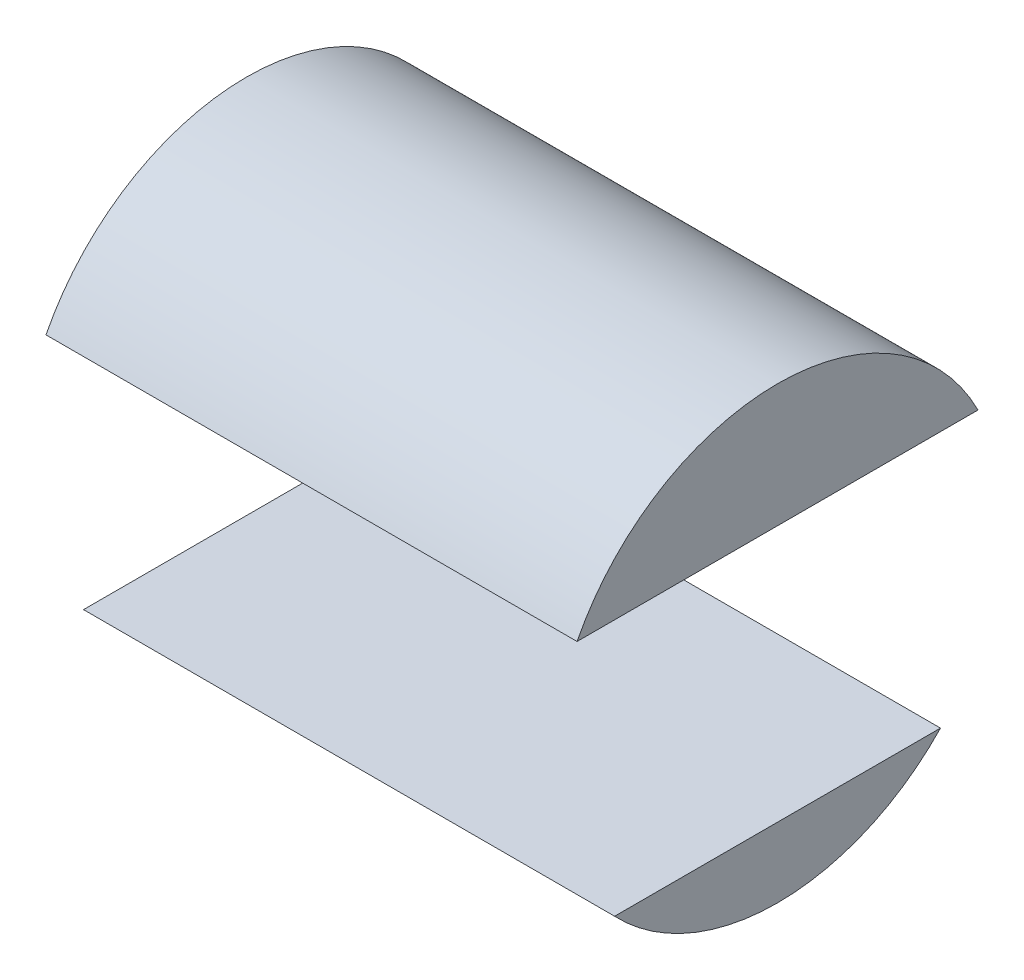
SolidWorks part; units mm, degrees
ref_plane "Front Plane" through (0, 0, 0) normal (0, 0, 1) x (1, 0, 0)
ref_plane "Top Plane" through (0, 0, 0) normal (0, 1, 0) x (1, 0, 0)
ref_plane "Right Plane" through (0, 0, 0) normal (1, 0, 0) x (0, 0, -1)
sketch "Sketch1" plane through (0, 0, 0) normal (1, 0, 0) x (0, 0, -1)
  line L0 (-30, -35) -> (30, -35)
  line L8 (30, 23) -> (-30, 23)
  line L9 (0, 23) -> (0, -35) construction
  line L15 (30, 23) -> (30, -35)
  line L16 (-30, -35) -> (-30, 23)
  circle A0 centre (0, 0) radius 50.8
  dimension "D2" = 60
  dimension "D4" = 101.6
  dimension "D1" = 35
  dimension "D3" = 60
  dimension "D5" = 23
extrude "Boss-Extrude1" add sketch "Sketch1" along normal blind 120
sketch "Sketch4" plane through (120, 0, 0) normal (1, 0, 0) x (0, 0, -1)
  line L0 (45.295, 23) -> (-45.295, 23)
  line L1 (30, 23) -> (-30, 23) construction
  line L2 (36.819, -35) -> (-36.819, -35)
  line L3 (-30, -35) -> (30, -35) construction
  line L4 (0, 23) -> (0, -35) construction
  circle A0 centre (0, 0) radius 50.8 construction
  arc A1 (-45.295, 23) -> (-36.819, -35) centre (0, 0) ccw
  arc A2 (45.295, 23) -> (36.819, -35) centre (0, 0) cw
extrude "Cut-Extrude1" cut sketch "Sketch4" against normal through all
